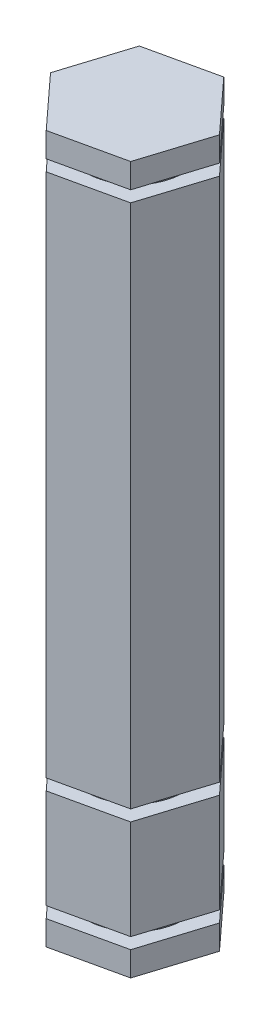
SolidWorks part; units mm, degrees
material "6061 Alloy"
ref_plane "Front Plane" through (0, 0, 0) normal (0, 0, 1) x (1, 0, 0)
ref_plane "Top Plane" through (0, 0, 0) normal (0, 1, 0) x (1, 0, 0)
ref_plane "Right Plane" through (0, 0, 0) normal (1, 0, 0) x (0, 0, -1)
sketch "Sketch1" plane through (0, 0, 0) normal (0, 1, 0) x (1, 0, 0)
  line L1 (4.9575, -5.4025) -> (7.1574, 1.592)
  line L2 (7.1574, 1.592) -> (2.2, 6.9945)
  line L3 (2.2, 6.9945) -> (-4.9575, 5.4025)
  line L4 (-4.9575, 5.4025) -> (-7.1574, -1.592)
  line L5 (-7.1574, -1.592) -> (-2.2, -6.9945)
  line L6 (-2.2, -6.9945) -> (4.9575, -5.4025)
  circle A0 centre (0, 0) radius 6.35 construction
  dimension "D1" = 12.7
extrude "Boss-Extrude1" add sketch "Sketch1" along normal blind 54.356
sketch "Sketch2" plane through (0, 54.356, 0) normal (0, 1, 0) x (1, 0, 0)
  circle A0 centre (0, 0) radius 5.0292
  dimension "D1" = 10.0584
extrude "Boss-Extrude2" add sketch "Sketch2" along normal blind 1.1684
sketch "Sketch3" plane through (0, 55.5244, 0) normal (0, 1, 0) x (1, 0, 0)
  line L6 (-2.2, -6.9945) -> (4.9575, -5.4025)
  line L7 (4.9575, -5.4025) -> (7.1574, 1.592)
  line L8 (7.1574, 1.592) -> (2.2, 6.9945)
  line L9 (2.2, 6.9945) -> (-4.9575, 5.4025)
  line L10 (-4.9575, 5.4025) -> (-7.1574, -1.592)
  line L11 (-7.1574, -1.592) -> (-2.2, -6.9945)
  line L12 (-2.2, -6.9945) -> (4.9575, -5.4025)
  line L13 (4.9575, -5.4025) -> (7.1574, 1.592)
  line L14 (7.1574, 1.592) -> (2.2, 6.9945)
  line L15 (2.2, 6.9945) -> (-4.9575, 5.4025)
  line L16 (-4.9575, 5.4025) -> (-7.1574, -1.592)
  line L17 (-7.1574, -1.592) -> (-2.2, -6.9945)
  dimension "D1" = 0
extrude "Boss-Extrude3" add sketch "Sketch3" along normal blind 2.54
sketch "Sketch4" plane through (0, 0, 0) normal (0, -1, 0) x (1, 0, 0)
  circle A0 centre (0, 0) radius 5.0292
  dimension "D1" = 10.0584
extrude "Boss-Extrude4" add sketch "Sketch4" along normal blind 1.1684
sketch "Sketch5" plane through (0, -1.1684, 0) normal (0, -1, 0) x (1, 0, 0)
  line L6 (4.9575, 5.4025) -> (-2.2, 6.9945)
  line L7 (-2.2, 6.9945) -> (-7.1574, 1.592)
  line L8 (-7.1574, 1.592) -> (-4.9575, -5.4025)
  line L9 (-4.9575, -5.4025) -> (2.2, -6.9945)
  line L10 (2.2, -6.9945) -> (7.1574, -1.592)
  line L11 (7.1574, -1.592) -> (4.9575, 5.4025)
  line L12 (4.9575, 5.4025) -> (-2.2, 6.9945)
  line L13 (-2.2, 6.9945) -> (-7.1574, 1.592)
  line L14 (-7.1574, 1.592) -> (-4.9575, -5.4025)
  line L15 (-4.9575, -5.4025) -> (2.2, -6.9945)
  line L16 (2.2, -6.9945) -> (7.1574, -1.592)
  line L17 (7.1574, -1.592) -> (4.9575, 5.4025)
  dimension "D1" = 0
extrude "Boss-Extrude5" add sketch "Sketch5" along normal blind 10.287
sketch "Sketch6" plane through (0, -11.4554, 0) normal (0, -1, 0) x (1, 0, 0)
  circle A0 centre (0, 0) radius 5.0292
  dimension "D1" = 10.0584
extrude "Boss-Extrude6" add sketch "Sketch6" along normal blind 1.1684
sketch "Sketch7" plane through (0, -12.6238, 0) normal (0, -1, 0) x (1, 0, 0)
  line L6 (7.1574, -1.592) -> (4.9575, 5.4025)
  line L7 (4.9575, 5.4025) -> (-2.2, 6.9945)
  line L8 (-2.2, 6.9945) -> (-7.1574, 1.592)
  line L9 (-7.1574, 1.592) -> (-4.9575, -5.4025)
  line L10 (-4.9575, -5.4025) -> (2.2, -6.9945)
  line L11 (2.2, -6.9945) -> (7.1574, -1.592)
  line L12 (7.1574, -1.592) -> (4.9575, 5.4025)
  line L13 (4.9575, 5.4025) -> (-2.2, 6.9945)
  line L14 (-2.2, 6.9945) -> (-7.1574, 1.592)
  line L15 (-7.1574, 1.592) -> (-4.9575, -5.4025)
  line L16 (-4.9575, -5.4025) -> (2.2, -6.9945)
  line L17 (2.2, -6.9945) -> (7.1574, -1.592)
  dimension "D1" = 0
extrude "Boss-Extrude7" add sketch "Sketch7" along normal blind 2.54
